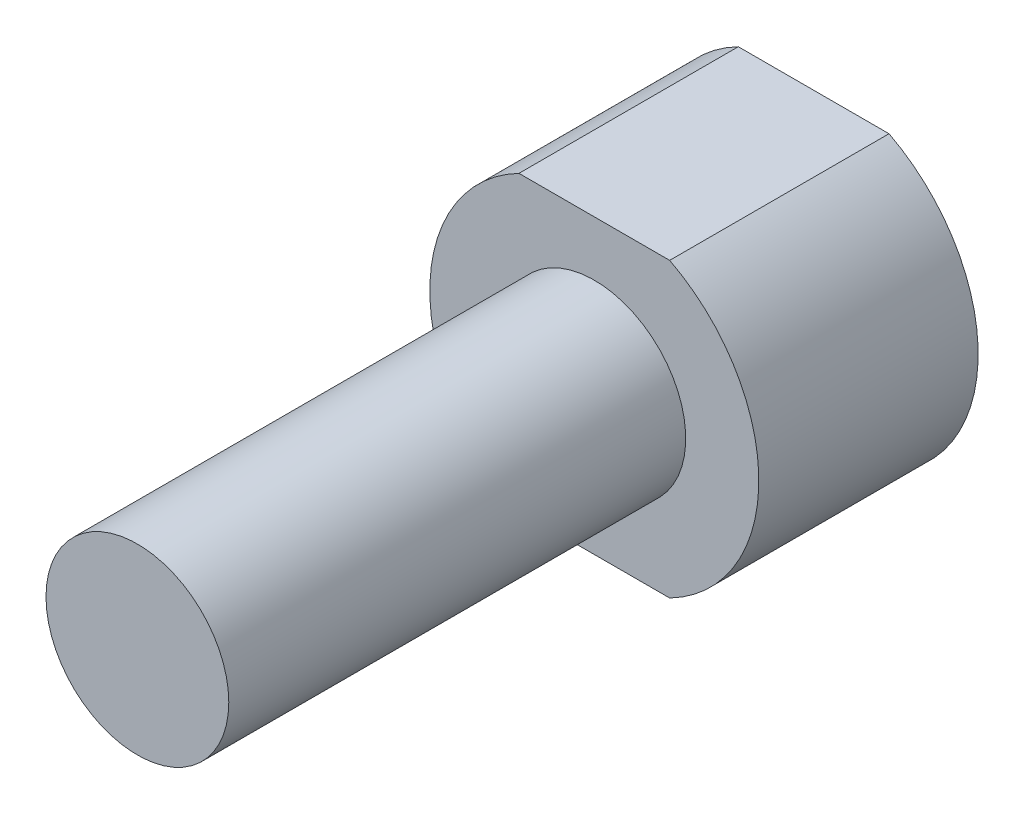
SolidWorks part; units mm, degrees
ref_plane "Plan de face" through (0, 0, 0) normal (0, 0, 1) x (1, 0, 0)
ref_plane "Plan de dessus" through (0, 0, 0) normal (0, 1, 0) x (1, 0, 0)
ref_plane "Plan de droite" through (0, 0, 0) normal (1, 0, 0) x (0, 0, -1)
sketch "Esquisse1" plane through (0, 0, 0) normal (0, 0, 1) x (1, 0, 0)
  line L0 (-12.5229, 8) -> (-9, 8) construction
  line L1 (-9, -8) -> (-12.5229, -8) construction
  line L2 (-12.5229, 0) -> (13.9382, 0) construction
  circle A0 centre (0, 0) radius 9 construction
  line B0 (-4.1231, 8) -> (4.1231, 8)
  line B1 (4.1231, -8) -> (-4.1231, -8)
  arc B2 (4.1231, 8) -> (4.1231, -8) centre (0, 0) cw
  arc B3 (-4.1231, 8) -> (-4.1231, -8) centre (0, 0) ccw
  dimension "D1" = 18
  dimension "D2" = 16
sketch_block_instance "Bloc1-1"
sketch_block "Bloc1"
extrude "Boss.-Extru.1" add sketch "Esquisse1" along normal blind 12
sketch "Esquisse2" plane through (0, 0, 12) normal (0, 0, 1) x (1, 0, 0)
  circle A0 centre (0, 0) radius 5
  dimension "D1" = 10
extrude "Boss.-Extru.2" add sketch "Esquisse2" along normal blind 25
